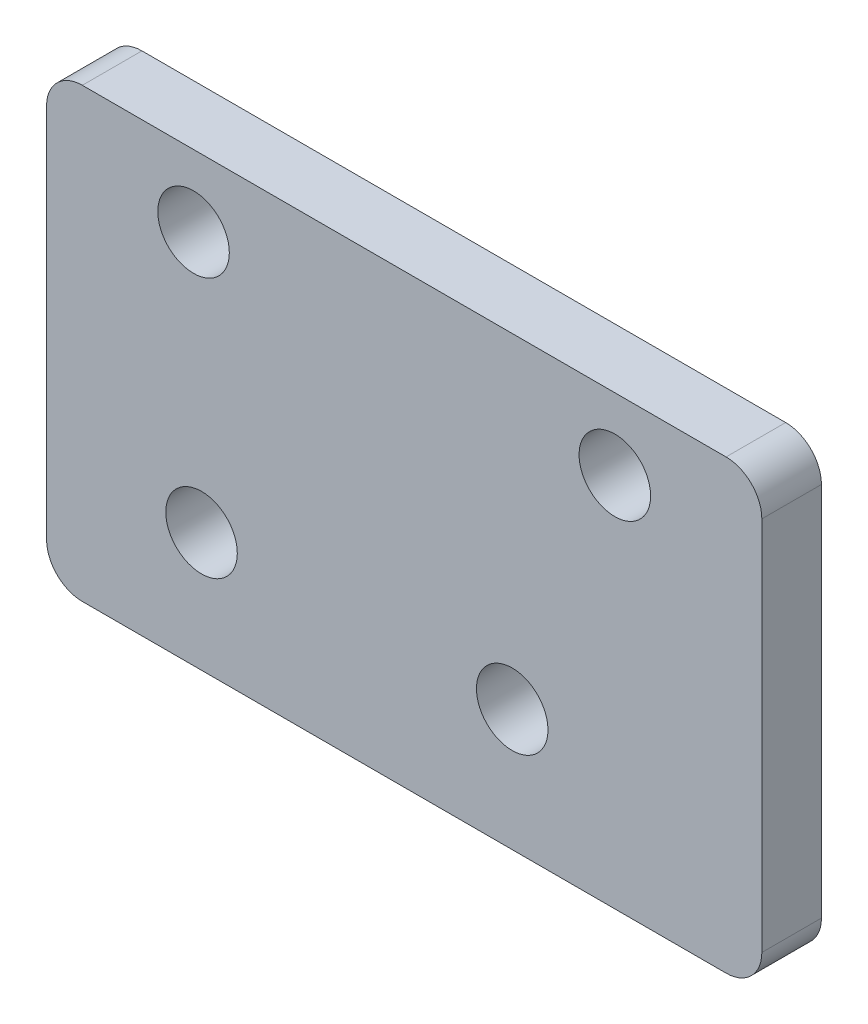
SolidWorks part; units mm, degrees
ref_plane "前视基准面" through (0, 0, 0) normal (0, 0, 1) x (1, 0, 0)
ref_plane "上视基准面" through (0, 0, 0) normal (0, 1, 0) x (1, 0, 0)
ref_plane "右视基准面" through (0, 0, 0) normal (1, 0, 0) x (0, 0, -1)
other "Configuration Table"
sketch "草图1" plane through (0, 0, 0) normal (0, 0, 1) x (1, 0, 0)
  line L0 (0, 0) -> (1.5, 0) construction
  line L2 (-15.5, 27.5) -> (38.5, 27.5)
  line L3 (-18.5, 24.5) -> (-18.5, -7)
  line L4 (-15.5, -10) -> (-8.825, -10)
  line L5 (41.5, 24.5) -> (41.5, -7)
  line L29 (33.3, -10) -> (38.5, -10)
  line L30 (31.175, -10) -> (-8.825, -10)
  line L34 (33.3, -10) -> (31.175, -10)
  arc A20 (38.5, 27.5) -> (41.5, 24.5) centre (38.5, 24.5) cw
  arc A21 (38.5, -10) -> (41.5, -7) centre (38.5, -7) ccw
  arc A22 (-18.5, -7) -> (-15.5, -10) centre (-15.5, -7) ccw
  arc A23 (-15.5, 27.5) -> (-18.5, 24.5) centre (-15.5, 24.5) ccw
  circle A32 centre (21.075, 0) radius 5.2518 construction
  dimension "D4" = 60
  dimension "D13" = 3
  dimension "D7" = 37.5
extrude "凸台-拉伸1" add sketch "草图1" along normal blind 5
sketch "草图2" plane through (0, 0, 5) normal (0, 0, 1) x (1, 0, 0)
  line L0 (21.075, 0) -> (21.075, 6.3806) construction
  line L1 (-15.5, 27.5) -> (38.5, 27.5) construction
  line L2 (11.5, 27.5) -> (11.5, 21.5) construction
  line L5 (29.17, 21.5) -> (-6.17, 21.5) construction
  circle A2 centre (-6.17, 21.5) radius 3
  circle A3 centre (29.17, 21.5) radius 3
  dimension "D1" = 6
  dimension "D5" = 6
  dimension "D3" = 35.34
extrude "切除-拉伸1" cut sketch "草图2" against normal blind 10 contours A2 | A3
sketch "草图4" plane through (0, 0, 5) normal (0, 0, 1) x (1, 0, 0)
  line L0 (41.5, 0) -> (21.5, 0) construction
  line L1 (41.5, 24.5) -> (41.5, -7) construction
  circle A0 centre (-5.5, 0) radius 3
  dimension "D3" = 6
  dimension "D2" = 27
extrude "切除-拉伸2" cut sketch "草图4" against normal blind 10
sketch "草图9" plane through (0, 0, 5) normal (0, 0, 1) x (1, 0, 0)
  circle A0 centre (20.56, 0.2) radius 3
extrude "切除-拉伸3" cut sketch "草图9" against normal blind 10
